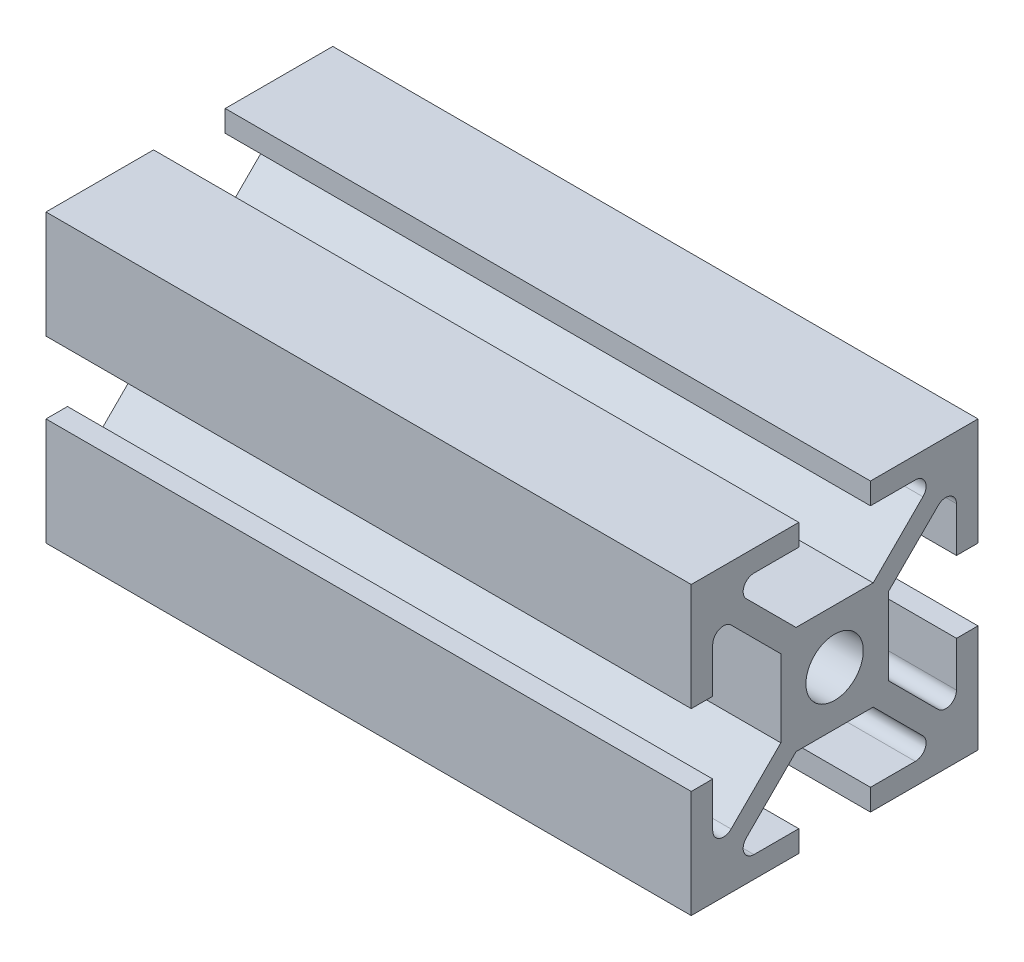
SolidWorks part; units mm, degrees
ref_plane "Plan de face" through (0, 0, 0) normal (0, 0, 1) x (1, 0, 0)
ref_plane "Plan de dessus" through (0, 0, 0) normal (0, 1, 0) x (1, 0, 0)
ref_plane "Plan de droite" through (0, 0, 0) normal (1, 0, 0) x (0, 0, -1)
sketch "Esquisse1" plane through (0, 0, 0) normal (1, 0, 0) x (0, 0, -1)
  line L0 (0, 0) -> (0, -14.4844) construction
  line L1 (-10, 10) -> (-2.5, 10)
  line L2 (-10, 10) -> (-10, 2.5)
  line L3 (-10, -10) -> (-2.5, -10)
  line L4 (10, 10) -> (10, 2.5)
  line L5 (-10, 10) -> (10, -10) construction
  line L6 (-10, -10) -> (10, 10) construction
  line L7 (-2.6893, 3.75) -> (2.6893, 3.75)
  line L8 (-3.75, 2.6893) -> (-3.75, -2.6893)
  line L9 (-2.6893, -3.75) -> (2.6893, -3.75)
  line L10 (3.75, 2.6893) -> (3.75, -2.6893)
  line L11 (-3.75, 3.75) -> (3.75, -3.75) construction
  line L12 (-3.75, -3.75) -> (3.75, 3.75) construction
  line L13 (-2.5, 8.5) -> (-2.5, 10)
  line L14 (2.5, 8.5) -> (2.5, 10)
  line L15 (8.5, 2.5) -> (10, 2.5)
  line L16 (8.5, -2.5) -> (10, -2.5)
  line L17 (-2.6893, 3.75) -> (-3.75, 3.75) construction
  line L18 (-7.4393, -8.5) -> (-2.6893, -3.75)
  line L19 (2.5, 8.5) -> (7.4393, 8.5)
  line L20 (7.4393, 8.5) -> (2.6893, 3.75)
  line L21 (-2.5, -8.5) -> (-7.4393, -8.5)
  line L22 (-2.5, 8.5) -> (-7.4393, 8.5)
  line L23 (-7.4393, 8.5) -> (-2.6893, 3.75)
  line L24 (8.5, 2.5) -> (8.5, 7.4393)
  line L25 (8.5, 7.4393) -> (3.75, 2.6893)
  line L26 (8.5, -7.4393) -> (3.75, -2.6893)
  line L27 (8.5, -2.5) -> (8.5, -7.4393)
  line L28 (8.5, -2.5) -> (10, -2.5)
  line L29 (0, 0) -> (19.7872, 0) construction
  line L30 (7.4393, -8.5) -> (2.6893, -3.75)
  line L31 (2.5, -8.5) -> (7.4393, -8.5)
  line L32 (2.5, -8.5) -> (2.5, -10)
  line L33 (-2.5, -8.5) -> (-2.5, -10)
  line L34 (-2.6893, -3.75) -> (2.6893, -3.75)
  line L35 (-8.5, -2.5) -> (-10, -2.5)
  line L36 (-8.5, -2.5) -> (-8.5, -7.4393)
  line L37 (-8.5, -7.4393) -> (-3.75, -2.6893)
  line L38 (-8.5, 7.4393) -> (-3.75, 2.6893)
  line L39 (-8.5, 2.5) -> (-8.5, 7.4393)
  line L40 (-8.5, -2.5) -> (-10, -2.5)
  line L41 (-8.5, 2.5) -> (-10, 2.5)
  line L42 (-3.75, 2.6893) -> (-3.75, -2.6893)
  line L43 (-10, -2.5) -> (-10, -10)
  line L44 (2.5, -10) -> (10, -10)
  line L45 (10, -2.5) -> (10, -10)
  line L46 (2.5, 10) -> (10, 10)
  circle A0 centre (0, 0) radius 2
  point P0 (0, 0)
  point P6 (0, 0)
  dimension "D10" = 4
  dimension "D1" = 20
  dimension "D2" = 1.5
  dimension "D3" = 5
  dimension "D4" = 7.5
  dimension "D5" = 1.5
  dimension "D6" = 1.5
  dimension "D7" = 0.75
  dimension "D8" = 5
  dimension "D9" = 20
extrude "Boss.-Extru.1" add sketch "Esquisse1" along normal blind 45 contours L46 L14 L19 L20 L7 L23 L22 L13 L1 L2 L41 L39 L38 L8 L37 L36 L35 L43 L3 L33 L21 L18 L9 L30 L31 L32 L44 L45 L16 L27 L26 L10 L25 L24 L15 L4 A0
fillet "Congé1" radius 0.75 8 edges at (22.5, -7.4393, 8.5) (22.5, -8.5, 7.4393) (22.5, -8.5, -7.4393) (22.5, -7.4393, -8.5) (22.5, 7.4393, -8.5) (22.5, 8.5, -7.4393) (22.5, 7.4393, 8.5) (22.5, 8.5, 7.4393)
